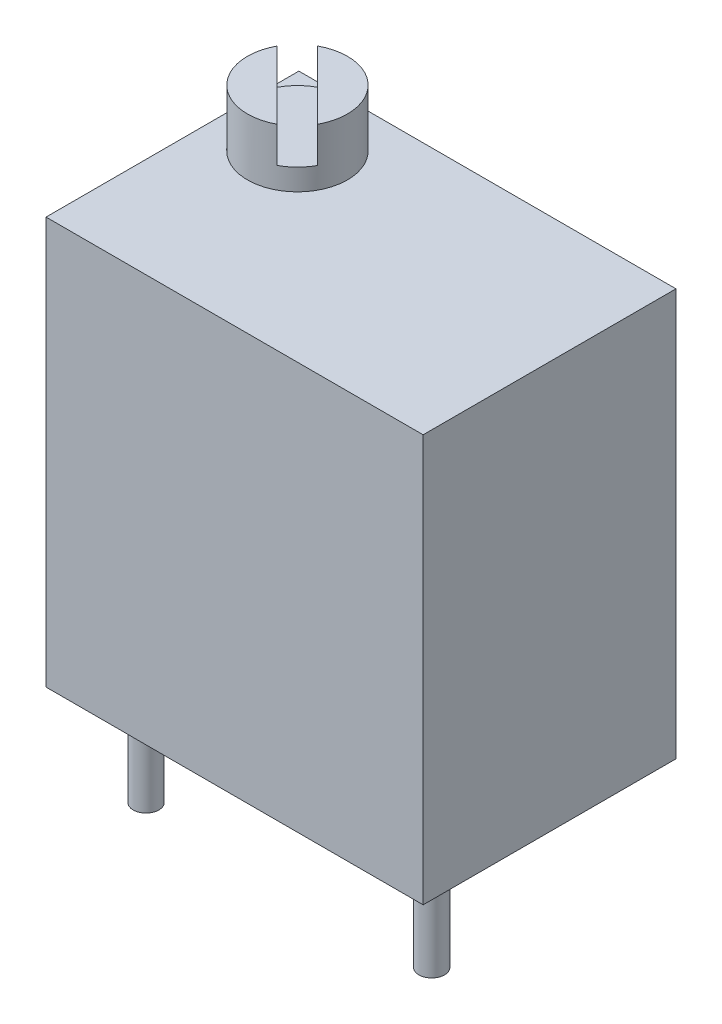
SolidWorks part; units mm, degrees
ref_plane "Front Plane" through (0, 0, 0) normal (0, 0, 1) x (1, 0, 0)
ref_plane "Top Plane" through (0, 0, 0) normal (0, 1, 0) x (1, 0, 0)
ref_plane "Right Plane" through (0, 0, 0) normal (1, 0, 0) x (0, 0, -1)
sketch "Sketch1" plane through (0, 0, 0) normal (0, 1, 0) x (1, 0, 0)
  line L1 (-0.762, -1.016) -> (5.9436, -1.016)
  line L2 (-0.762, -1.016) -> (-0.762, 3.4798)
  line L3 (-0.762, 3.4798) -> (5.9436, 3.4798)
  line L4 (5.9436, -1.016) -> (5.9436, 3.4798)
  dimension "D1" = 6.7056
  dimension "D2" = 4.4958
  dimension "D3" = 0.762
  dimension "D4" = 1.016
extrude "Extrude1" add sketch "Sketch1" along normal blind 7.239
sketch "Sketch2" plane through (0, 7.239, 0) normal (0, 1, 0) x (1, 0, 0)
  line L0 (-0.762, 3.4798) -> (-0.762, -1.016) construction
  line L1 (5.9436, 3.4798) -> (-0.762, 3.4798) construction
  circle A0 centre (0.4572, 2.2352) radius 0.889
  dimension "D3" = 1.778
  dimension "D1" = 1.2192
  dimension "D2" = 1.2446
extrude "Extrude2" add sketch "Sketch2" along normal blind 1.016
sketch "Sketch3" plane through (0, 8.255, 0) normal (0, 1, 0) x (1, 0, 0)
  line L0 (-0.4501, 2.7833) -> (1.0053, 1.3279)
  line L1 (-0.4501, 2.7833) -> (-0.0909, 3.1425)
  line L2 (1.0053, 1.3279) -> (1.3645, 1.6871)
  line L3 (-0.0909, 3.1425) -> (1.3645, 1.6871)
  line L4 (-0.4501, 2.7833) -> (1.3645, 1.6871) construction
  line L5 (1.0053, 1.3279) -> (-0.0909, 3.1425) construction
  line L6 (-0.762, 3.4798) -> (-0.762, -1.016) construction
  point P1 (0.4572, 2.2352)
  dimension "D1" = 0.508
  dimension "D2" = 45
extrude "Extrude3" cut sketch "Sketch3" against normal blind 0.635
sketch "Sketch4" plane through (0, 0, 0) normal (0, -1, 0) x (1, 0, 0)
  circle A0 centre (0, 0) radius 0.2286
  circle A1 centre (5.08, 0) radius 0.2286
  circle A2 centre (2.54, -2.54) radius 0.2286
  dimension "D4" = 0.4572
  dimension "D1" = 2.54
  dimension "D2" = 2.54
  dimension "D3" = 2.54
extrude "Extrude4" add sketch "Sketch4" along normal blind 4.7752
sketch "Sketch5" plane through (0, 0, 1.016) normal (0, 0, 1) x (1, 0, 0)
  line L0 (-0.2286, -4.7752) -> (0.2286, -4.7752) construction
  line L1 (-0.2286, -4.7752) -> (5.3086, -4.7752)
  line L2 (-0.2286, -4.7752) -> (-0.2286, -1.905)
  line L3 (-0.2286, -1.905) -> (5.3086, -1.905)
  line L4 (5.3086, -4.7752) -> (5.3086, -1.905)
  line L5 (5.3086, -4.7752) -> (5.3086, 0) construction
  line L6 (-0.2286, 0) -> (-0.2286, -4.7752) construction
  line L7 (-0.762, 0) -> (5.9436, 0) construction
  dimension "D1" = 1.905
extrude "PCB Trim" cut sketch "Sketch5" against normal through all
